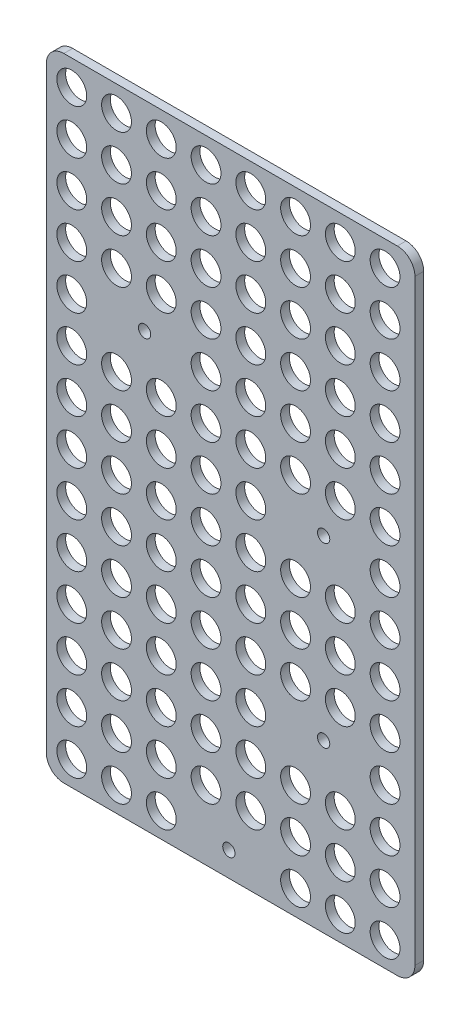
SolidWorks part; units mm, degrees
ref_plane "Front Plane" through (0, 0, 0) normal (0, 0, 1) x (1, 0, 0)
ref_plane "Top Plane" through (0, 0, 0) normal (0, 1, 0) x (1, 0, 0)
ref_plane "Right Plane" through (0, 0, 0) normal (1, 0, 0) x (0, 0, -1)
sketch "Sketch1" plane through (0, 0, 0) normal (0, 0, 1) x (1, 0, 0)
  line L1 (0, 180) -> (105, 180)
  line L2 (0, 180) -> (0, 0)
  line L3 (0, 0) -> (105, 0)
  line L4 (105, 180) -> (105, 0)
  circle A0 centre (28, 123) radius 1.75
  circle A1 centre (79, 98) radius 1.75
  circle A2 centre (79, 47.5) radius 1.75
  circle A3 centre (52, 7) radius 1.75
  point P13 (0, 0)
  point P14 (0, 0)
  dimension "D3" = 3.5
  dimension "D1" = 105
  dimension "D2" = 180
  dimension "D4" = 28
  dimension "D5" = 52
  dimension "D6" = 7
  dimension "D7" = 79
  dimension "D8" = 47.5
  dimension "D9" = 98
  dimension "D10" = 123
extrude "Boss-Extrude1" add sketch "Sketch1" along normal blind 2.5
fillet "Fillet2" radius 5 4 edges at (0, 0, 1.25) (105, 0, 1.25) (105, 180, 1.25) (0, 180, 1.25)
sketch "Sketch2" plane through (0, 0, 2.5) normal (0, 0, 1) x (1, 0, 0)
  line L0 (100, 180) -> (5, 180) construction
  circle A0 centre (7.25, 172.75) radius 4.25
  dimension "D1" = 8.5
  dimension "D2" = 7.25
  dimension "D3" = 7.25
extrude "Cut-Extrude1" cut sketch "Sketch2" against normal up to next
pattern_linear "LPattern1" count 8 spacing 12.75 along (1, 0, 0) count 14 spacing 12.75 along (0, -1, 0) skipping (1, 4), (2, 4), (3, 13), (4, 13), (5, 6), (5, 10), (6, 6), (6, 10) of "Cut-Extrude1"
equation "\"D2@Sketch2\"=\"D3@Sketch2\""
